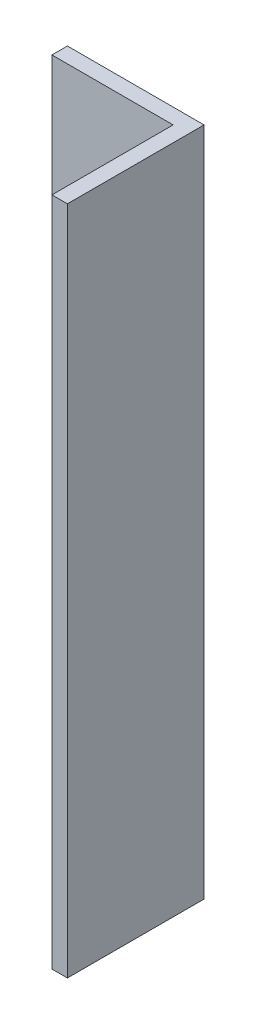
SolidWorks part; units mm, degrees
ref_plane "Front Plane" through (0, 0, 0) normal (0, 0, 1) x (1, 0, 0)
ref_plane "Top Plane" through (0, 0, 0) normal (0, 1, 0) x (1, 0, 0)
ref_plane "Right Plane" through (0, 0, 0) normal (1, 0, 0) x (0, 0, -1)
sketch "Sketch1" plane through (0, 0, 0) normal (0, 1, 0) x (1, 0, 0)
  line L0 (0, 0) -> (26.5, 0)
  line L1 (26.5, 0) -> (26.5, -26.5)
  line L2 (26.5, -26.5) -> (23.5, -26.5)
  line L3 (23.5, -26.5) -> (23.5, -3)
  line L4 (23.5, -3) -> (0, -3)
  line L5 (0, -3) -> (0, 0)
  dimension "D1" = 26.5
  dimension "D2" = 26.5
  dimension "D3" = 3
  dimension "D4" = 3
extrude "Boss-Extrude1" add sketch "Sketch1" along normal blind 130
